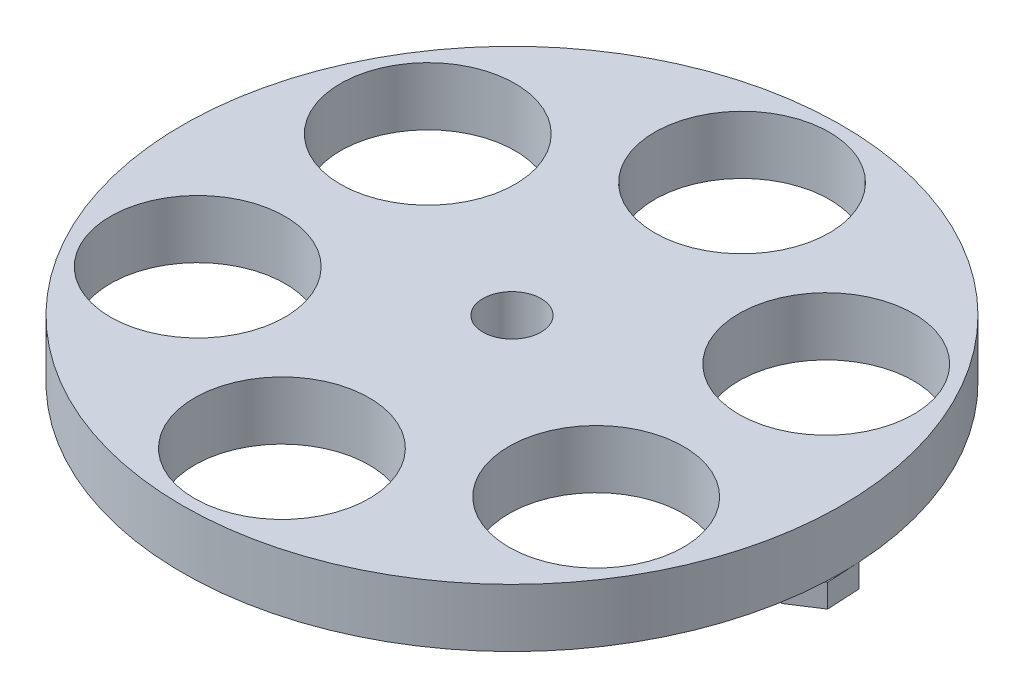
SolidWorks part; units mm, degrees
ref_plane "Alzado" through (0, 0, 0) normal (0, 0, 1) x (1, 0, 0)
ref_plane "Planta" through (0, 0, 0) normal (0, 1, 0) x (1, 0, 0)
ref_plane "Vista lateral" through (0, 0, 0) normal (1, 0, 0) x (0, 0, -1)
sketch "Croquis1" plane through (0, 0, 0) normal (0, 1, 0) x (1, 0, 0)
  circle A0 centre (0, 0) radius 113.2284
  circle A1 centre (0, 79.0502) radius 30
  circle A2 centre (68.4595, 39.5251) radius 30
  circle A3 centre (68.4595, -39.5251) radius 30
  circle A4 centre (0, -79.0502) radius 30
  circle A5 centre (-68.4595, -39.5251) radius 30
  circle A6 centre (-68.4595, 39.5251) radius 30
  circle A7 centre (0, 0) radius 10
  point P10 (0, 0)
  point P11 (0, 0)
  point P12 (0, 0)
  point P24 (0, 0)
  point P30 (0, 0)
  point P31 (0, 0)
  point P32 (0, 0)
  dimension "D3" = 6
extrude "Saliente-Extruir2" add sketch "Croquis1" along normal blind 20
sketch "Croquis2" plane through (0, 0, 0) normal (0, -1, 0) x (1, 0, 0)
  line L1 (113.057, -6.2277) -> (113.6517, 5.1977)
  line L2 (113.6517, 5.1977) -> (104.0544, 11.4254)
  line L3 (104.0544, 11.4254) -> (93.8624, 6.2277)
  line L4 (93.8624, 6.2277) -> (93.2677, -5.1977)
  line L5 (93.2677, -5.1977) -> (102.865, -11.4254)
  line L6 (102.865, -11.4254) -> (113.057, -6.2277)
  circle A0 centre (103.4597, 0) radius 9.9081 construction
extrude "Saliente-Extruir3" add sketch "Croquis2" along normal blind 8
